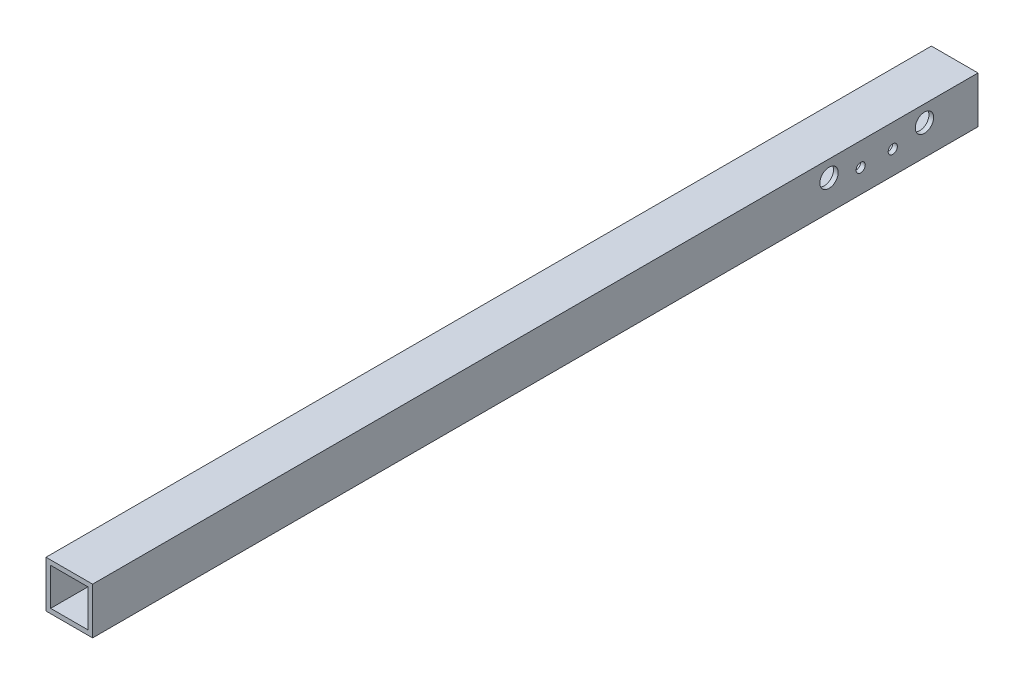
SolidWorks part; units mm, degrees
material "6063-O, Extruded Rod (SS)"
ref_plane "Front Plane" through (0, 0, 0) normal (0, 0, 1) x (1, 0, 0)
ref_plane "Top Plane" through (0, 0, 0) normal (0, 1, 0) x (1, 0, 0)
ref_plane "Right Plane" through (0, 0, 0) normal (1, 0, 0) x (0, 0, -1)
sketch "Sketch1" plane through (0, 0, 0) normal (0, 0, 1) x (1, 0, 0)
  line L0 (-10.16, 10.16) -> (10.16, 10.16)
  line L1 (-12.7, -12.7) -> (12.7, -12.7)
  line L2 (-12.7, -12.7) -> (-12.7, 12.7)
  line L3 (-12.7, 12.7) -> (12.7, 12.7)
  line L4 (12.7, -12.7) -> (12.7, 12.7)
  line L5 (-12.7, -12.7) -> (12.7, 12.7) construction
  line L6 (-12.7, 12.7) -> (12.7, -12.7) construction
  line L7 (10.16, -10.16) -> (10.16, 10.16)
  line L8 (-10.16, -10.16) -> (10.16, -10.16)
  line L9 (-10.16, -10.16) -> (-10.16, 10.16)
  point P0 (0, 0)
  dimension "D1" = 25.4
  dimension "D2" = 25.4
  dimension "D3" = 2.54
extrude "Boss-Extrude1" add sketch "Sketch1" along normal mid plane 482.6
ref_plane "Plane1" through (-12.7, 0, 0) normal (-1, 0, 0) x (0, 0, 1)
sketch "Sketch2" plane through (-12.7, 0, 0) normal (-1, 0, 0) x (0, 0, 1)
  line L0 (-228.6, 3.81) -> (-143.6, 3.81) construction
  line L2 (241.3, -12.7) -> (241.3, 12.7) construction
  line L3 (-160.1, 3.81) -> (-212.1, 3.81) construction
  line L4 (241.3, -12.7) -> (-241.3, -12.7) construction
  circle A0 centre (-212.1, 3.81) radius 5
  circle A1 centre (-160.1, 3.81) radius 5
  point P15 (-186.1, 3.81)
  dimension "D1" = 10
  dimension "D2" = 10
  dimension "D3" = 52
  dimension "D4" = 469.9
  dimension "D5" = 85
  dimension "D6" = 16.51
extrude "Cut-Extrude1" cut sketch "Sketch2" against normal through all both and the other way through all
sketch "Sketch4" plane through (-12.7, 0, 0) normal (-1, 0, 0) x (0, 0, 1)
  circle A0 centre (-212.1, 3.81) radius 2.5
  circle A1 centre (-160.1, 3.81) radius 2.5
  circle A2 centre (-212.1, 3.81) radius 5 construction
  circle A3 centre (-160.1, 3.81) radius 5 construction
  dimension "D1" = 5
extrude "Cut-Extrude2" [suppressed] cut sketch "Sketch4" against normal through all both and the other way through all
sketch "Sketch5" plane through (-12.7, 0, 0) normal (-1, 0, 0) x (0, 0, 1)
  line L0 (-160.1, 0) -> (-177.35, 0) construction
  line L1 (-212.1, 0) -> (-194.85, 0) construction
  line L2 (-177.35, 0) -> (-186.1, 0) construction
  line L3 (-160.1, 0) -> (-160.1, 3.81) construction
  line L4 (-212.1, 3.81) -> (-212.1, 0) construction
  line L5 (-186.1, 0) -> (-194.85, 0) construction
  line L6 (241.3, -12.7) -> (-241.3, -12.7) construction
  circle A0 centre (-194.85, 0) radius 2.5
  circle A1 centre (-177.35, 0) radius 2.5
  point P13 (-186.1, 0)
  dimension "D1" = 5
  dimension "D2" = 17.5
  dimension "D3" = 12.7
extrude "Cut-Extrude3" cut sketch "Sketch5" against normal through all both and the other way through all
